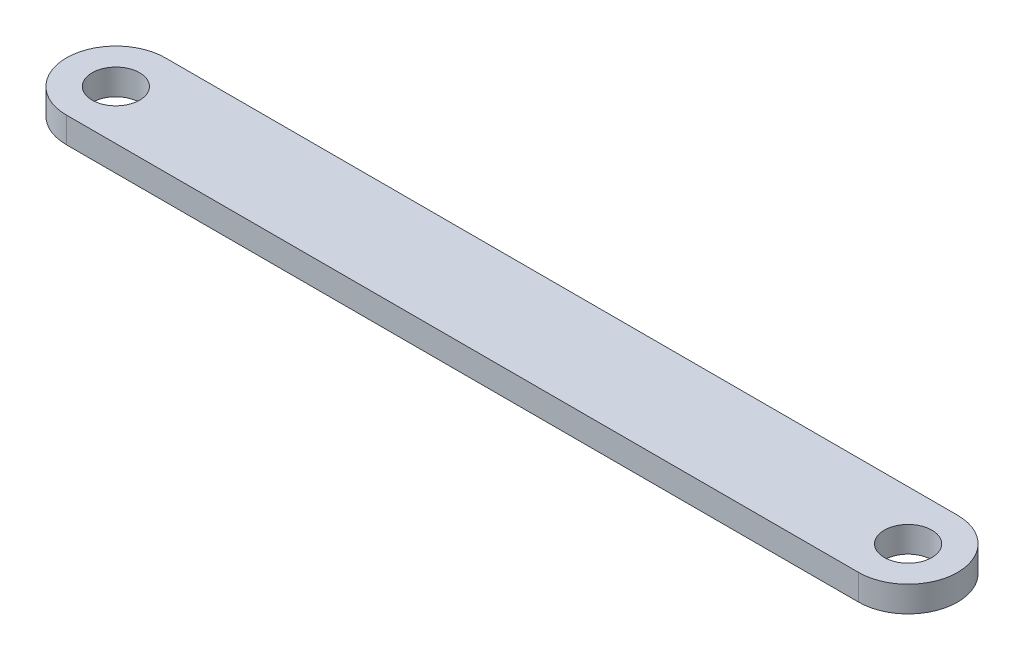
SolidWorks part; units mm, degrees
material "AISI 1015 Steel, Cold Drawn (SS)"
ref_plane "Front Plane" through (0, 0, 0) normal (0, 0, 1) x (1, 0, 0)
ref_plane "Top Plane" through (0, 0, 0) normal (0, 1, 0) x (1, 0, 0)
ref_plane "Right Plane" through (0, 0, 0) normal (1, 0, 0) x (0, 0, -1)
sketch "Sketch1" plane through (0, 0, 0) normal (0, 1, 0) x (1, 0, 0)
  line L0 (100, 0) -> (-100, 0) construction
  line L1 (100, -12.5) -> (-100, -12.5)
  line L2 (100, 12.5) -> (-100, 12.5)
  arc A0 (100, -12.5) -> (100, 12.5) centre (100, 0) ccw
  arc A1 (-100, 12.5) -> (-100, -12.5) centre (-100, 0) ccw
  circle A2 centre (-100, 0) radius 6
  circle A3 centre (100, 0) radius 6
  point P2 (0, 0)
  dimension "D1" = 200
  dimension "D3" = 12
  dimension "D2" = 25
extrude "Boss-Extrude1" add sketch "Sketch1" along normal blind 6.5
